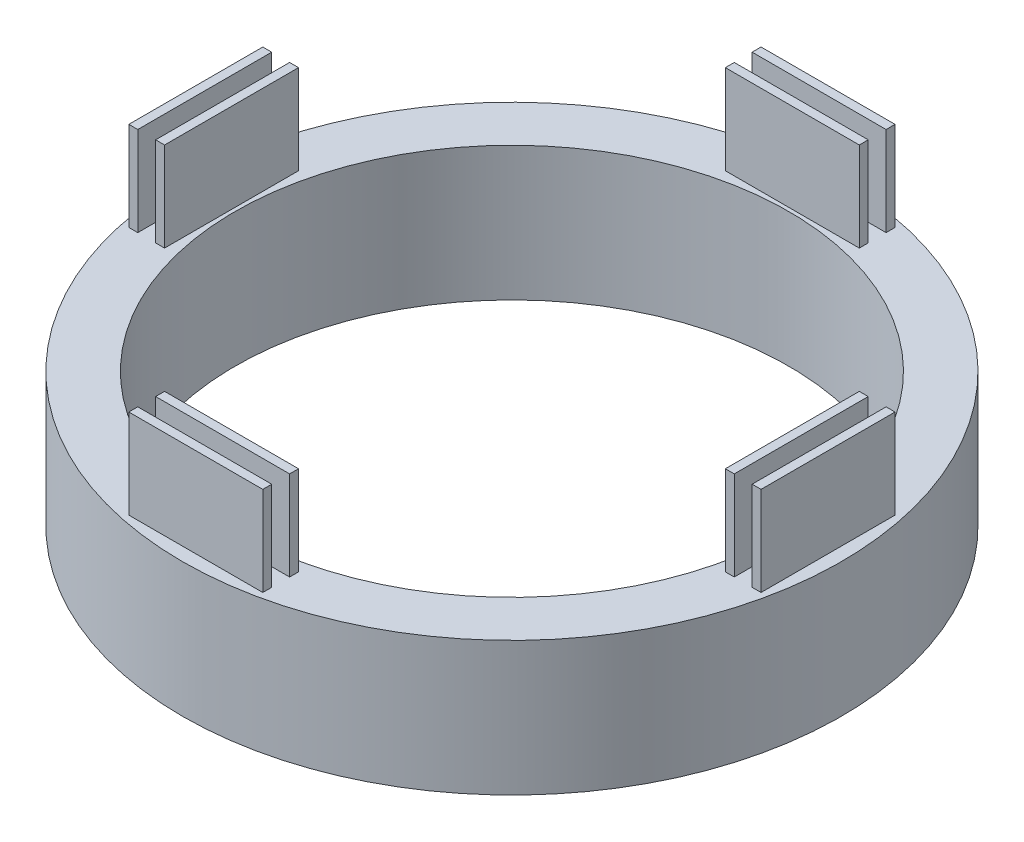
SolidWorks part; units mm, degrees
material "3.0205 (EN-AW 1200)"
ref_plane "Plan de face" through (0, 0, 0) normal (0, 0, 1) x (1, 0, 0)
ref_plane "Plan de dessus" through (0, 0, 0) normal (0, 1, 0) x (1, 0, 0)
ref_plane "Plan de droite" through (0, 0, 0) normal (1, 0, 0) x (0, 0, -1)
sketch "Esquisse1" plane through (0, 0, 0) normal (0, 1, 0) x (1, 0, 0)
  circle A0 centre (0, 0) radius 62
  circle A1 centre (0, 0) radius 73.8
  dimension "D1" = 147.6
  dimension "D2" = 124
extrude "Boss.-Extru.1" add sketch "Esquisse1" along normal blind 30
sketch "Esquisse2" plane through (0, 30, 0) normal (0, 1, 0) x (1, 0, 0)
  line L0 (-109.0313, 0) -> (186.0934, 0) construction
  line L1 (-70.7864, 15) -> (-62.7864, 15)
  line L2 (-70.7864, 15) -> (-70.7864, -15)
  line L3 (-70.7864, -15) -> (-62.7864, -15)
  line L4 (-62.7864, 15) -> (-62.7864, -15)
  line L5 (15, 70.7864) -> (-15, 70.7864)
  line L6 (-68.7864, 15) -> (-64.7864, 15)
  line L7 (-68.7864, 15) -> (-68.7864, -15)
  line L8 (-68.7864, -15) -> (-64.7864, -15)
  line L9 (-64.7864, 15) -> (-64.7864, -15)
  line L10 (15, 68.7864) -> (-15, 68.7864)
  line L11 (15, 64.7864) -> (-15, 64.7864)
  line L12 (15, 62.7864) -> (-15, 62.7864)
  line L13 (-15, 70.7864) -> (-15, 62.7864)
  line L14 (15, 70.7864) -> (15, 62.7864)
  line L15 (70.7864, -15) -> (70.7864, 15)
  line L16 (68.7864, -15) -> (68.7864, 15)
  line L17 (64.7864, -15) -> (64.7864, 15)
  line L18 (62.7864, -15) -> (62.7864, 15)
  line L19 (70.7864, 15) -> (62.7864, 15)
  line L20 (70.7864, -15) -> (62.7864, -15)
  line L21 (-15, -70.7864) -> (15, -70.7864)
  line L22 (-15, -68.7864) -> (15, -68.7864)
  line L23 (-15, -64.7864) -> (15, -64.7864)
  line L24 (-15, -62.7864) -> (15, -62.7864)
  line L25 (15, -70.7864) -> (15, -62.7864)
  line L26 (-15, -70.7864) -> (-15, -62.7864)
  point P38 (0, 0)
  dimension "D1" = 30
  dimension "D2" = 8
  dimension "D3" = 15
  dimension "D4" = 4
  dimension "D5" = 2
  dimension "D6" = 4
extrude "Boss.-Extru.2" add sketch "Esquisse2" along normal blind 20 contours L2 L0 L7 L1 | L0 L2 L3 L7 | L0 L9 L3 L4 | L9 L0 L4 L1 | L14 L5 L13 L10 | L14 L11 L13 L12 | L0 L18 L20 L17 | L18 L0 L17 L19 | L16 L0 L15 L19 | L0 L16 L20 L15 | L26 L21 L25 L22 | L26 L23 L25 L24
